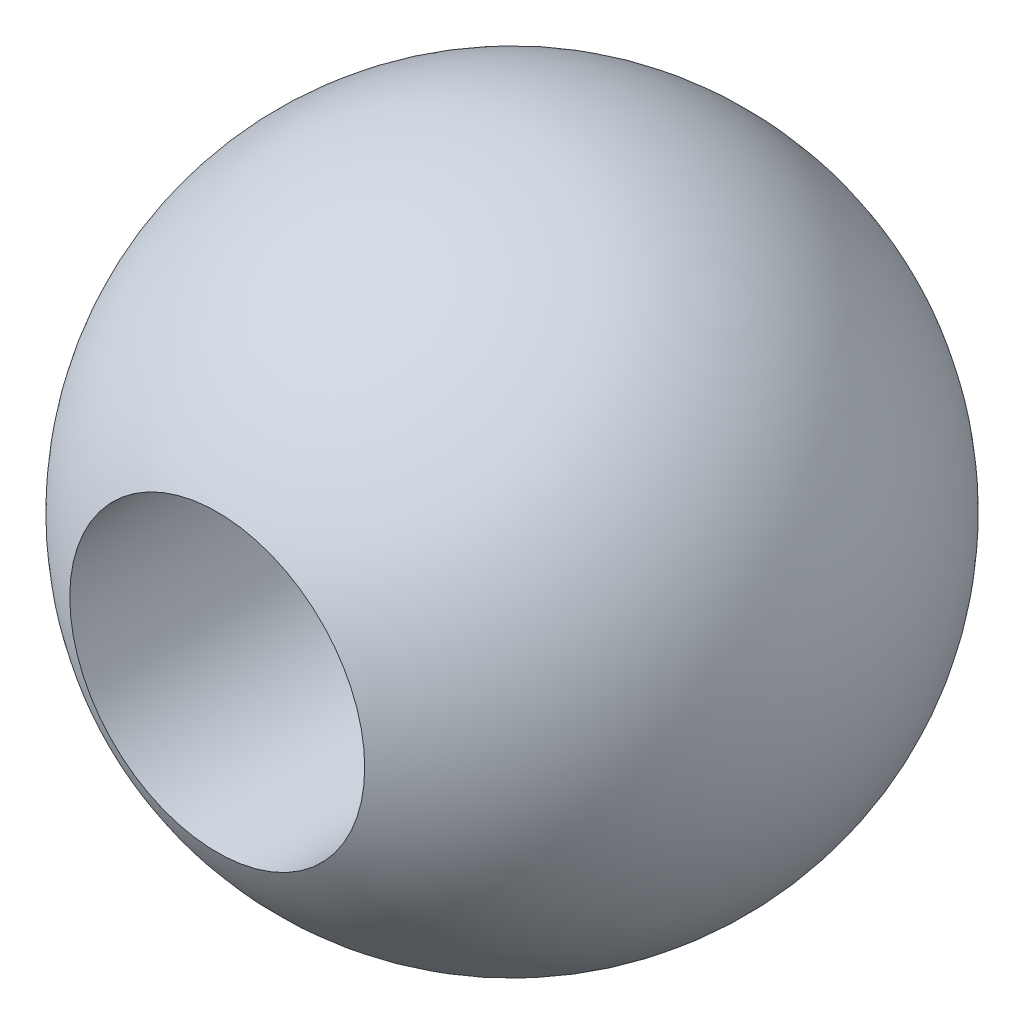
SolidWorks part; units mm, degrees
ref_plane "Front Plane" through (0, 0, 0) normal (0, 0, 1) x (1, 0, 0)
ref_plane "Top Plane" through (0, 0, 0) normal (0, 1, 0) x (1, 0, 0)
ref_plane "Right Plane" through (0, 0, 0) normal (1, 0, 0) x (0, 0, -1)
sketch "Sketch1" plane through (0, 0, 0) normal (0, 0, 1) x (1, 0, 0)
  line L0 (0, 7.5) -> (0, -7.5) construction
  line L1 (0, 7.5) -> (0, -7.5)
  arc A0 (0, 7.5) -> (0, -7.5) centre (0, 0) ccw
  dimension "D1" = 15
ref_plane "Plane1" through (0, 0, 30) normal (0, 0, 1) x (1, 0, 0)
revolve "Revolve1" add sketch "Sketch1" angle 360 about L0
sketch "Sketch3" plane through (0, 0, 30) normal (0, 0, 1) x (1, 0, 0)
  circle A0 centre (0, 0) radius 3.3553
extrude "Cut-Extrude2" cut sketch "Sketch3" against normal blind 59
